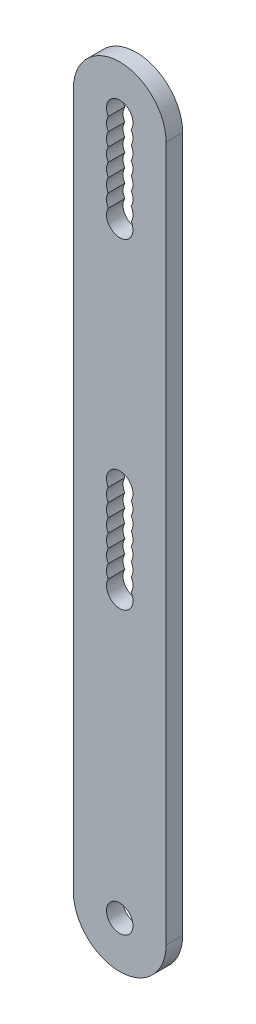
SolidWorks part; units mm, degrees
ref_plane "Front Plane" through (0, 0, 0) normal (1, 0, 0) x (0, 1, 0)
ref_plane "Top Plane" through (0, 0, 0) normal (0, 0, 1) x (0, 1, 0)
ref_plane "Right Plane" through (0, 0, 0) normal (0, 1, 0) x (-1, 0, 0)
sketch "Sketch1" plane through (0, 0, 0) normal (0, 0, 1) x (0, 1, 0)
  line L0 (105, 0) -> (-105, 0) construction
  line L1 (-105, 14) -> (105, 14)
  line L2 (-105, -14) -> (105, -14)
  line L3 (105, 0) -> (101, 0) construction
  line L4 (0, 0) -> (73, 0) construction
  line L5 (0, 0) -> (135.3038, 0) construction
  line L6 (0, 0) -> (4, 0) construction
  circle A1 centre (-105, 0) radius 4
  arc A2 (103, -3.4641) -> (103, 3.4641) centre (105, 0) ccw
  arc A3 (-105, 14) -> (-105, -14) centre (-105, 0) ccw
  arc A4 (105, -14) -> (105, 14) centre (105, 0) ccw
  circle A5 centre (105, 0) radius 14 construction
  circle A6 centre (-105, 0) radius 14 construction
  arc A7 (99, -3.4641) -> (103, -3.4641) centre (101, 0) ccw
  arc A8 (95, -3.4641) -> (99, -3.4641) centre (97, 0) ccw
  arc A9 (91, -3.4641) -> (95, -3.4641) centre (93, 0) ccw
  arc A10 (87, -3.4641) -> (91, -3.4641) centre (89, 0) ccw
  arc A11 (83, -3.4641) -> (87, -3.4641) centre (85, 0) ccw
  arc A12 (79, -3.4641) -> (83, -3.4641) centre (81, 0) ccw
  arc A13 (79, 3.4641) -> (79, -3.4641) centre (77, 0) ccw
  arc A14 (83, 3.4641) -> (79, 3.4641) centre (81, 0) ccw
  arc A15 (87, 3.4641) -> (83, 3.4641) centre (85, 0) ccw
  arc A16 (91, 3.4641) -> (87, 3.4641) centre (89, 0) ccw
  arc A17 (95, 3.4641) -> (91, 3.4641) centre (93, 0) ccw
  arc A18 (99, 3.4641) -> (95, 3.4641) centre (97, 0) ccw
  circle A19 centre (105, 0) radius 4 construction
  arc A20 (103, 3.4641) -> (99, 3.4641) centre (101, 0) ccw
  circle A21 centre (0, 0) radius 4
  circle A22 centre (4, 0) radius 4
  circle A23 centre (8, 0) radius 4
  circle A24 centre (0, 0) radius 4
  circle A25 centre (4, 0) radius 4
  circle A26 centre (-4, 0) radius 4
  circle A27 centre (0, 0) radius 4
  circle A28 centre (-8, 0) radius 4
  circle A29 centre (-4, 0) radius 4
  circle A30 centre (-12, 0) radius 4
  circle A31 centre (-8, 0) radius 4
  circle A32 centre (-16, 0) radius 4
  circle A33 centre (-12, 0) radius 4
  circle A34 centre (-4, 0) radius 4
  circle A35 centre (-8, 0) radius 4
  circle A36 centre (-12, 0) radius 4
  circle A37 centre (-16, 0) radius 4
  circle A38 centre (-20, 0) radius 4
  point P5 (0, 0)
  dimension "D1" = 8
  dimension "D6" = 3
  dimension "D2" = 210
  dimension "D5" = 4
  dimension "D8" = 4
  dimension "D3" = 10
  dimension "D4" = 8
  dimension "D7" = 6
extrude "Boss-Extrude1" add sketch "Sketch1" along normal mid plane 5 contours L2 A4 L1 A3 A38 A32 A30 A28 A26 A21 A22 A23 A20 A2 A7 A8 A9 A10 A11 A12 A13 A14 A15 A16 A17 A18 A1
